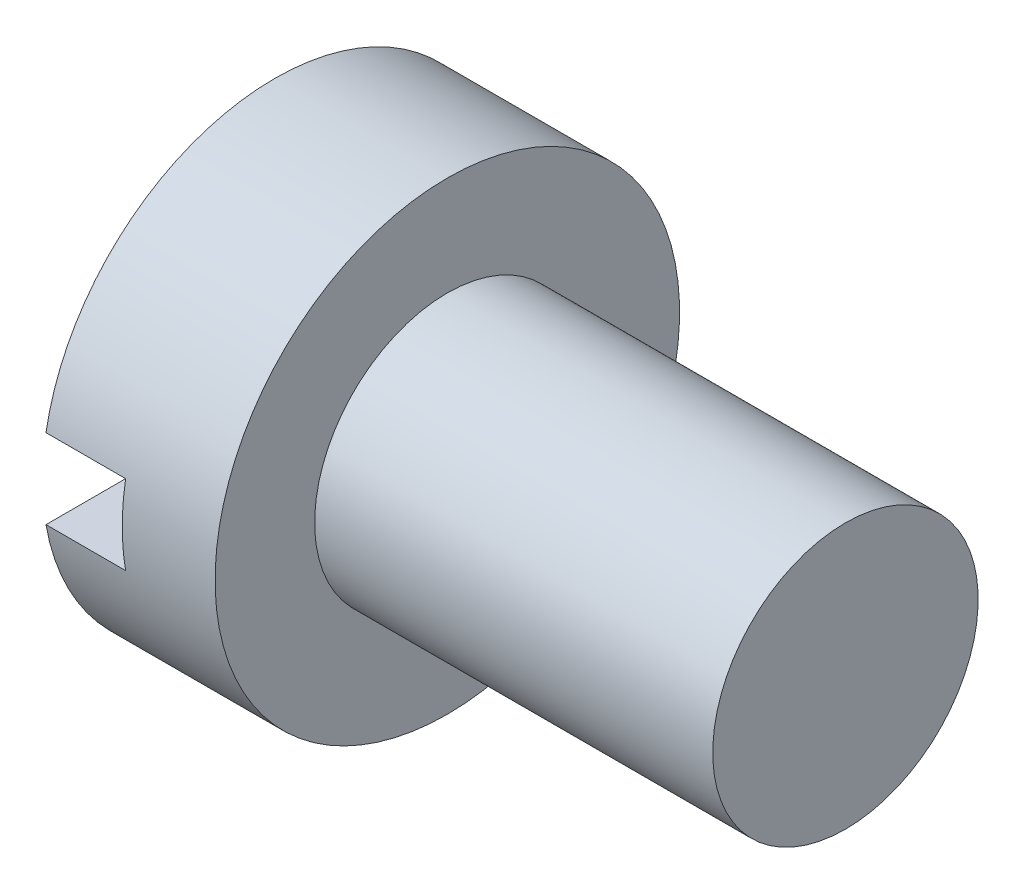
SolidWorks part; units mm, degrees
material "Plain Carbon Steel"
ref_plane "Front Plane" through (0, 0, 0) normal (0, 0, 1) x (1, 0, 0)
ref_plane "Top Plane" through (0, 0, 0) normal (0, 1, 0) x (1, 0, 0)
ref_plane "Right Plane" through (0, 0, 0) normal (1, 0, 0) x (0, 0, -1)
sketch "Sketch1" plane through (0, 0, 0) normal (0, 0, 1) x (1, 0, 0)
  line L0 (0, 0) -> (0, 3.5)
  line L1 (0, 3.5) -> (2.6, 3.5)
  line L2 (2.6, 3.5) -> (2.6, 2)
  line L3 (2.6, 2) -> (8.6, 2)
  line L4 (8.6, 2) -> (8.6, 0)
  line L5 (8.6, 0) -> (0, 0) construction
  line L6 (0, 0) -> (8.6, 0)
  dimension "D1" = 4
  dimension "D2" = 6
  dimension "D3" = 7
  dimension "D4" = 2.6
revolve "Revolve1" add sketch "Sketch1" angle 360 about L5
sketch "Sketch2" plane through (0, 0, 0) normal (-1, 0, 0) x (0, 0, 1)
  line L0 (3.5, 0) -> (-3.5, 0) construction
  line L1 (-3.5, 0.6) -> (3.5, 0.6)
  line L2 (-3.5, 0.6) -> (-3.5, -0.6)
  line L3 (-3.5, -0.6) -> (3.5, -0.6)
  line L4 (3.5, 0.6) -> (3.5, -0.6)
  circle A0 centre (0, 0) radius 3.5 construction
  dimension "D1" = 1.2
extrude "Cut-Extrude1" cut sketch "Sketch2" against normal blind 1.2
